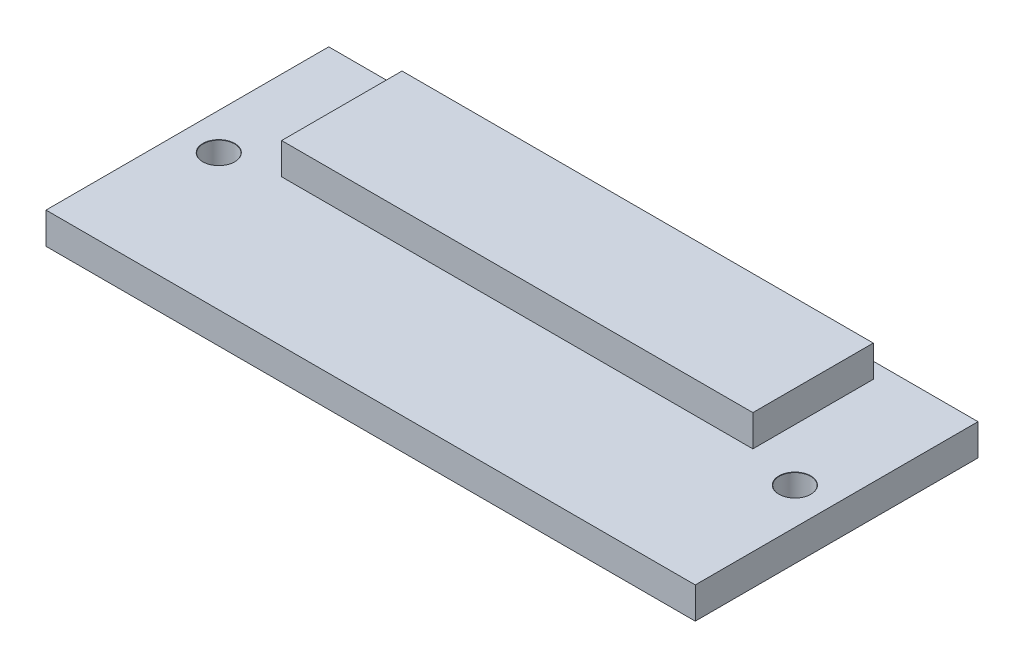
SolidWorks part; units mm, degrees
ref_plane "Front Plane" through (0, 0, 0) normal (0, 0, 1) x (1, 0, 0)
ref_plane "Top Plane" through (0, 0, 0) normal (0, 1, 0) x (1, 0, 0)
ref_plane "Right Plane" through (0, 0, 0) normal (1, 0, 0) x (0, 0, -1)
sketch "Sketch1" plane through (0, 0, 0) normal (0, 1, 0) x (1, 0, 0)
  line L1 (0, 0) -> (62, 0)
  line L2 (0, 0) -> (0, 27)
  line L3 (0, 27) -> (62, 27)
  line L4 (62, 0) -> (62, 27)
  dimension "D1" = 62
  dimension "D2" = 27
extrude "Boss-Extrude1" add sketch "Sketch1" along normal blind 3
sketch "Sketch2" plane through (0, 3, 0) normal (0, 1, 0) x (1, 0, 0)
  line L0 (0, 27) -> (0, 0) construction
  line L2 (62, 27) -> (0, 27) construction
  circle A0 centre (3.5, 13) radius 1.5
  circle A1 centre (58.5, 13.0142) radius 1.5
  point P4 (0, 0)
  point P5 (0, 0)
  point P6 (4.3693, 16.4442)
  point P7 (0, 0)
  point P8 (0, 0)
  point P9 (0, 0)
  point P12 (0, 0)
  point P14 (5.3441, 27)
  dimension "D2" = 55
  dimension "D1" = 3.5
  dimension "D3" = 14
hole_wizard "Ø3.0mm Dowel Hole1" positions "Sketch3" profile "Sketch4" hole size "Ø3.0" standard "ISO" end condition through all
sketch "Sketch3" plane through (0, 3, 0) normal (0, 1, 0) x (1, 0, 0)
  point P0 (3.5, 13)
  point P3 (58.5, 13.0142)
sketch "Sketch4" plane through (3.5, 3, -13) normal (1, 0, 0) x (0, 0, 1)
  line L0 (0, 0) -> (0, 3)
  line L1 (0, 3) -> (1.5, 3)
  line L2 (1.5, 3) -> (1.5, 0.025)
  line L3 (1.5, 0.025) -> (1.525, 0)
  line L5 (1.525, 0) -> (0, 0)
  line L6 (-1.5, 0.025) -> (-1.525, 0) construction
  line L11 (0, -6.35) -> (0, 107.95) construction
  dimension "Thru Hole Dia." = 3
  dimension "Thru Hole Depth" = 3
  dimension "Near C'Sink Dia." = 3.05
  dimension "Near C'Sink Angle" = 90
sketch "Sketch5" plane through (0, 3, 0) normal (0, 1, 0) x (1, 0, 0)
  line L0 (62, 27) -> (0, 27) construction
  line L1 (8.5, 25.5) -> (53.5, 25.5)
  line L2 (8.5, 25.5) -> (8.5, 14)
  line L3 (8.5, 14) -> (53.5, 14)
  line L4 (53.5, 25.5) -> (53.5, 14)
  line L5 (0, 27) -> (0, 0) construction
  dimension "D1" = 1.5
  dimension "D2" = 13
  dimension "D3" = 45
  dimension "D4" = 8.5
extrude "Cut-Extrude1" cut sketch "Sketch5" against normal through all
sketch "Sketch6" plane through (0, 3, 0) normal (0, 1, 0) x (1, 0, 0)
  line L1 (8.5, 25.5) -> (53.5, 25.5)
  line L2 (8.5, 25.5) -> (8.5, 14)
  line L3 (8.5, 14) -> (53.5, 14)
  line L4 (53.5, 25.5) -> (53.5, 14)
extrude "Boss-Extrude2" add sketch "Sketch6" along normal blind 3 separate body
